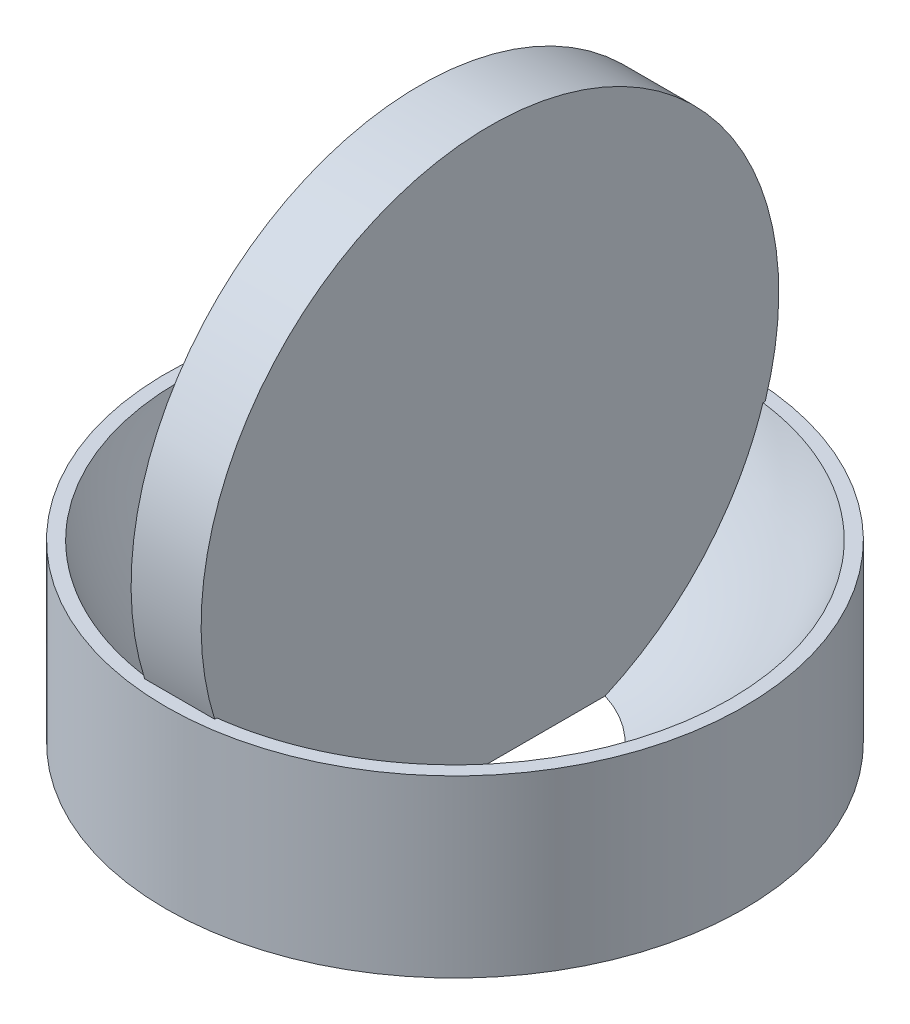
SolidWorks part; units mm, degrees
ref_plane "Front Plane" through (0, 0, 0) normal (0, 0, 1) x (1, 0, 0)
ref_plane "Top Plane" through (0, 0, 0) normal (0, 1, 0) x (1, 0, 0)
ref_plane "Right Plane" through (0, 0, 0) normal (1, 0, 0) x (0, 0, -1)
sketch "Croquis1" plane through (0, 0, 0) normal (0, 1, 0) x (1, 0, 0)
  circle A0 centre (0, 0) radius 8.25
  dimension "D1" = 16.5
extrude "Saliente-Extruir1" add sketch "Croquis1" along normal blind 5
ref_plane "Plano1" through (8.25, 0, 0) normal (1, 0, 0) x (0, 0, -1)
ref_plane "Plano2" through (0, 2.4, 0) normal (0, -1, 0) x (-1, 0, 0)
ref_plane "Plano3" through (0, 0, -8.35) normal (0, 0, 1) x (1, 0, 0)
ref_plane "Plano4" through (0, 0, 8.35) normal (0, 0, 1) x (1, 0, 0)
ref_plane "Plano5" through (0, 7.5, 0) normal (0, 1, 0) x (1, 0, 0)
sketch "Croquis10" plane through (0, 7.5, 0) normal (0, 1, 0) x (1, 0, 0)
  line L0 (0, 8.25) -> (0, -8.25)
  circle A0 centre (0, 0) radius 8.25 construction
  arc A1 (0, 8.25) -> (0, -8.25) centre (0, 0) cw
revolve "Cortar-Revolución1" cut sketch "Croquis10" angle 360 about L0
sketch "Croquis11" plane through (0, 0, 0) normal (1, 0, 0) x (0, 0, -1)
  line L0 (2.3828, 7.5) -> (-2.3828, 7.5) construction
  circle A0 centre (0, 7.5) radius 8.25
  dimension "D1" = 16.5
extrude "Saliente-Extruir2" add sketch "Croquis11" along normal mid plane 2
sketch "Croquis13" plane through (0, 0, -8.35) normal (0, 0, 1) x (1, 0, 0)
  line L1 (-8.25, 0) -> (8.2419, 0)
  line L2 (-8.25, 0) -> (-8.25, -1.5923)
  line L3 (-8.25, -1.5923) -> (8.2419, -1.5923)
  line L4 (8.2419, 0) -> (8.2419, -1.5923)
extrude "Cortar-Extruir11" cut sketch "Croquis13" along normal through all
